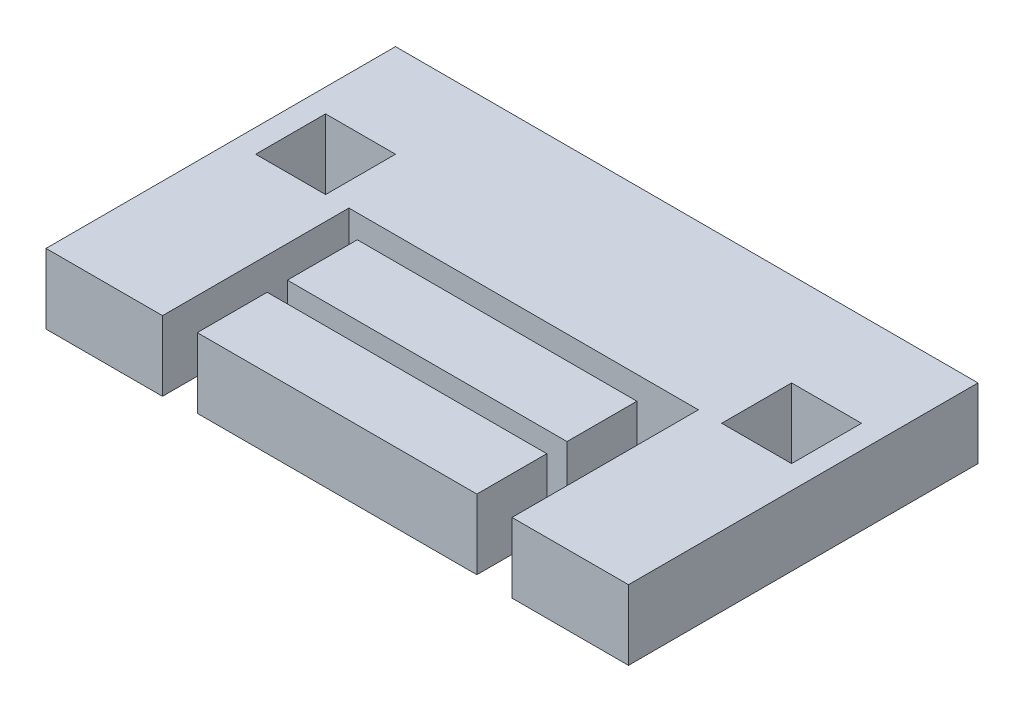
SolidWorks part; units mm, degrees
ref_plane "Front Plane" through (0, 0, 0) normal (0, 0, 1) x (1, 0, 0)
ref_plane "Top Plane" through (0, 0, 0) normal (0, 1, 0) x (1, 0, 0)
ref_plane "Right Plane" through (0, 0, 0) normal (1, 0, 0) x (0, 0, -1)
sketch "Sketch1" plane through (0, 0, 0) normal (0, 1, 0) x (1, 0, 0)
  line L0 (-18.8038, 19.5918) -> (-18.8038, 4.5918)
  line L1 (-18.8038, 4.5918) -> (-13.8038, 4.5918)
  line L2 (-13.8038, 4.5918) -> (-13.8038, 12.5918)
  line L3 (-13.8038, 12.5918) -> (1.1962, 12.5918)
  line L4 (1.1962, 12.5918) -> (1.1962, 4.5918)
  line L5 (1.1962, 4.5918) -> (6.1962, 4.5918)
  line L6 (6.1962, 4.5918) -> (6.1962, 19.5918)
  line L7 (-18.8038, 19.5918) -> (6.1962, 19.5918)
  line L8 (-6.3038, 19.5918) -> (-6.3038, 12.5918) construction
  line L9 (-17.8038, 15.5918) -> (-14.8038, 15.5918)
  line L10 (-17.8038, 15.5918) -> (-17.8038, 12.5918)
  line L11 (-17.8038, 12.5918) -> (-14.8038, 12.5918)
  line L12 (-14.8038, 15.5918) -> (-14.8038, 12.5918)
  line L13 (2.1962, 15.5918) -> (2.1962, 12.5918)
  line L14 (5.1962, 12.5918) -> (2.1962, 12.5918)
  line L15 (5.1962, 15.5918) -> (5.1962, 12.5918)
  line L16 (5.1962, 15.5918) -> (2.1962, 15.5918)
  line L17 (-12.427, 7.7072) -> (-0.427, 7.7072)
  line L18 (-12.4434, 11.5918) -> (-0.4434, 11.5918)
  line L19 (-12.4434, 11.5918) -> (-12.4434, 8.5918)
  line L20 (-12.4434, 8.5918) -> (-0.4434, 8.5918)
  line L21 (-0.4434, 11.5918) -> (-0.4434, 8.5918)
  line L22 (-12.427, 7.7072) -> (-12.427, 4.7072)
  line L23 (-12.427, 4.7072) -> (-0.427, 4.7072)
  line L24 (-0.427, 7.7072) -> (-0.427, 4.7072)
  point P22 (0, 0)
  point P23 (-16.8038, 6.8263)
  point P24 (0, 0)
  dimension "D1" = 5
  dimension "D2" = 8
  dimension "D3" = 15
  dimension "D4" = 3
  dimension "D5" = 3
  dimension "D6" = 1
  dimension "D7" = 3
  dimension "D8" = 12
  dimension "D9" = 15
  dimension "D10" = 1
  dimension "D11" = 3
extrude "Boss-Extrude1" add sketch "Sketch1" along normal blind 3 contours L8 L7 L0 L1 L2 L3 L9 L12 L11 L10 | L7 L8 L3 L4 L5 L6 L16 L15 L14 L13 | L2 L20 L4 L18 | L24 L17 L22 L23
